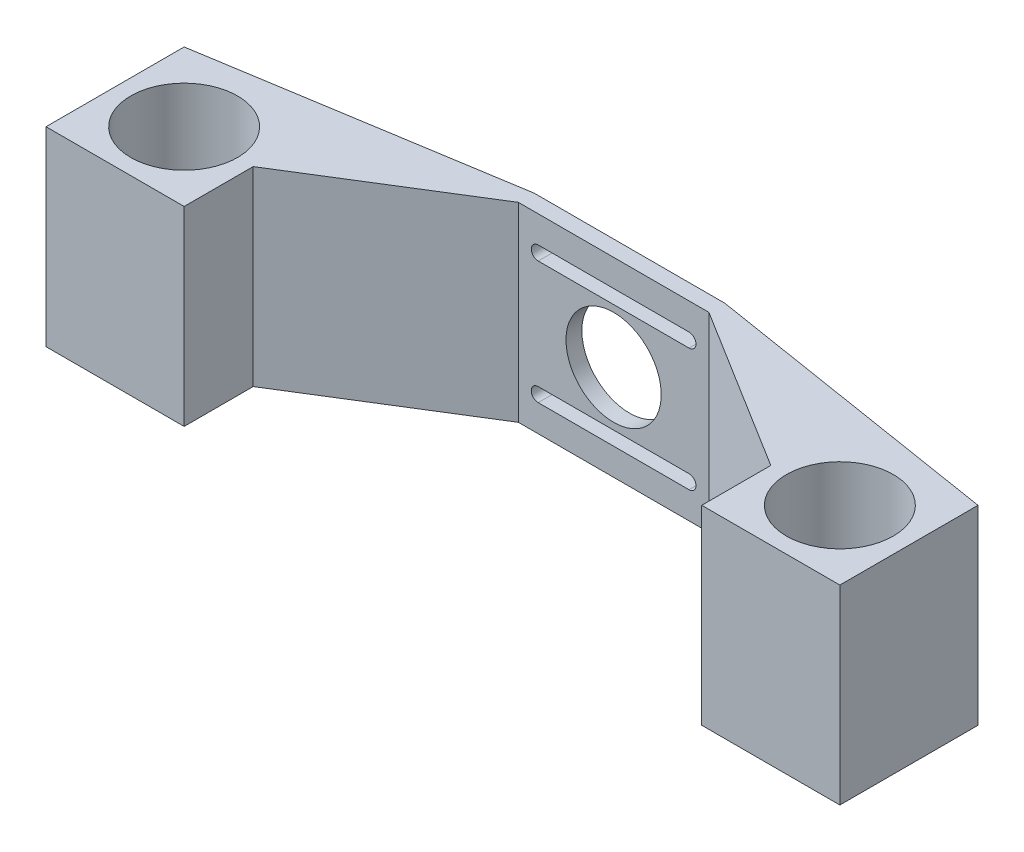
SolidWorks part; units mm, degrees
ref_plane "Front Plane" through (0, 0, 0) normal (0, 0, 1) x (1, 0, 0)
ref_plane "Top Plane" through (0, 0, 0) normal (0, 1, 0) x (1, 0, 0)
ref_plane "Right Plane" through (0, 0, 0) normal (1, 0, 0) x (0, 0, -1)
sketch "Sketch2" plane through (0, 0, 0) normal (0, 1, 0) x (1, 0, 0)
  line L0 (-17.4, -17.4) -> (82.6, -17.4) construction
  line L1 (-17.4, -17.4) -> (17.4, -17.4)
  line L2 (-17.4, -17.4) -> (-17.4, 17.4)
  line L5 (0, 17.4) -> (0, -17.4) construction
  line L6 (-17.4, 0) -> (17.4, 0) construction
  line L7 (82.6, -17.4) -> (82.6, 29.6) construction
  line L8 (17.4, -17.4) -> (17.4, 0)
  line L9 (82.6, 29.6) -> (58.6, 29.6)
  line L10 (82.6, 29.6) -> (82.6, 25.6)
  line L11 (82.6, 25.6) -> (58.6, 25.6)
  line L13 (17.4, 0) -> (58.6, 25.6)
  line L14 (58.6, 29.6) -> (-17.4, 17.4)
  circle A0 centre (0, 0) radius 13.45
  point P0 (0, 0)
  dimension "D3" = 26.9
  dimension "D8" = 17.4
  dimension "D9" = 17.4
  dimension "D1" = 34.8
  dimension "D2" = 34.8
  dimension "D4" = 100
  dimension "D5" = 47
  dimension "D6" = 24
  dimension "D7" = 4
extrude "Boss-Extrude1" add sketch "Sketch2" along normal blind 48
sketch3d "3DSketch1"
  line L0 (82.6, 0, -29.6) -> (82.6, 0, -25.6) construction
  line L1 (82.6, 0, -25.6) -> (82.6, 48, -25.6) construction
ref_plane "Plane1" through (82.6, 0, 0) normal (1, 0, 0) x (0, 0, -1)
mirror "Mirror1" about plane through (82.6, 0, 0) normal (1, 0, 0) of "Boss-Extrude1"
sketch "Sketch4" plane through (0, 0, -29.6) normal (0, 0, -1) x (-1, 0, 0)
  line L0 (-106.6, 24) -> (-58.6, 24) construction
  line L1 (-58.6, 48) -> (-58.6, 0) construction
  line L2 (-101.6, 8.55) -> (-63.6, 8.55) construction
  line L3 (-101.6, 10.3) -> (-63.6, 10.3)
  line L4 (-82.6, 0) -> (-82.6, 48) construction
  line L5 (-101.6, 6.8) -> (-63.6, 6.8)
  line L6 (-101.6, 39.45) -> (-63.6, 39.45) construction
  line L7 (-101.6, 37.7) -> (-63.6, 37.7)
  line L8 (-101.6, 41.2) -> (-63.6, 41.2)
  arc A0 (-101.6, 10.3) -> (-101.6, 6.8) centre (-101.6, 8.55) ccw
  arc A1 (-63.6, 6.8) -> (-63.6, 10.3) centre (-63.6, 8.55) ccw
  arc A2 (-101.6, 37.7) -> (-101.6, 41.2) centre (-101.6, 39.45) cw
  arc A3 (-63.6, 41.2) -> (-63.6, 37.7) centre (-63.6, 39.45) cw
  circle A4 centre (-82.6, 24) radius 12
  point P5 (-82.6, 24)
  point P7 (-82.6, 8.55)
  point P17 (-82.6, 39.45)
  dimension "D4" = 24
  dimension "D1" = 15.45
  dimension "D2" = 1.75
  dimension "D3" = 38
extrude "Cut-Extrude1" cut sketch "Sketch4" against normal blind 48
